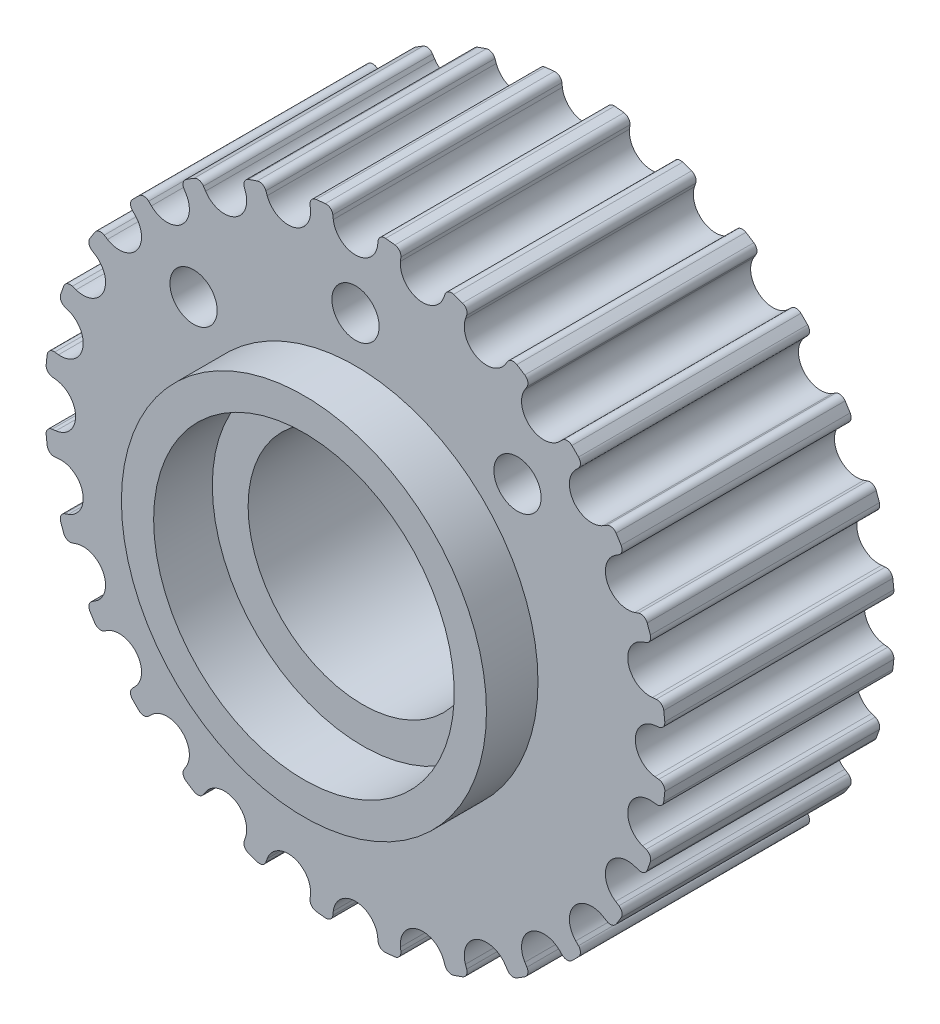
SolidWorks part; units mm, degrees
material "6061 合金"
ref_plane "前视基准面" through (0, 0, 0) normal (0, 0, 1) x (1, 0, 0)
ref_plane "上视基准面" through (0, 0, 0) normal (0, 1, 0) x (1, 0, 0)
ref_plane "右视基准面" through (0, 0, 0) normal (1, 0, 0) x (0, 0, -1)
sketch "草图2" plane through (0, 0, 0) normal (0, 0, 1) x (1, 0, 0)
  line L36 (1.3319, 20.7804) -> (1.2989, 20.5118)
  line L37 (-1.7978, 20.5118) -> (-1.8308, 20.7804)
  line L38 (-3.4222, 20.6011) -> (-3.3946, 20.3319)
  line L39 (-6.4137, 19.6428) -> (-6.5056, 19.8973)
  line L40 (-8.0172, 19.3684) -> (-7.9303, 19.1121)
  line L41 (-10.7204, 17.7684) -> (-10.8667, 17.9962)
  line L42 (-12.2227, 17.1441) -> (-12.081, 16.9135)
  line L43 (-14.5021, 14.9827) -> (-14.6954, 15.1722)
  line L44 (-15.8278, 14.0398) -> (-15.6383, 13.8465)
  line L45 (-17.5691, 11.4254) -> (-17.7997, 11.5671)
  line L46 (-18.6517, 10.2111) -> (-18.424, 10.0648)
  line L47 (-19.7676, 7.2748) -> (-20.024, 7.3616)
  line L48 (-20.5529, 5.85) -> (-20.2983, 5.7581)
  line L49 (-20.9874, 2.739) -> (-21.2567, 2.7666)
  line L50 (-21.436, 1.1752) -> (-21.1673, 1.1423)
  line L51 (-21.1673, -1.9545) -> (-21.436, -1.9875)
  line L52 (-21.2567, -3.5789) -> (-20.9874, -3.5512)
  line L53 (-20.2983, -6.5703) -> (-20.5529, -6.6623)
  line L54 (-20.024, -8.1739) -> (-19.7676, -8.087)
  line L55 (-18.424, -10.8771) -> (-18.6517, -11.0234)
  line L56 (-17.7997, -12.3793) -> (-17.5691, -12.2376)
  line L57 (-15.6383, -14.6588) -> (-15.8278, -14.8521)
  line L58 (-14.6954, -15.9845) -> (-14.5021, -15.795)
  line L59 (-12.081, -17.7258) -> (-12.2227, -17.9564)
  line L60 (-10.8667, -18.8084) -> (-10.7204, -18.5807)
  line L61 (-7.9303, -19.9243) -> (-8.0172, -20.1806)
  line L62 (-6.5056, -20.7096) -> (-6.4137, -20.455)
  line L63 (-3.3946, -21.1441) -> (-3.4222, -21.4133)
  line L64 (-1.8308, -21.5926) -> (-1.7978, -21.324)
  line L65 (1.2989, -21.324) -> (1.3319, -21.5926)
  line L66 (2.9233, -21.4133) -> (2.8957, -21.1441)
  line L67 (5.9148, -20.455) -> (6.0067, -20.7096)
  line L68 (7.5183, -20.1806) -> (7.4314, -19.9243)
  line L69 (10.2215, -18.5807) -> (10.3678, -18.8084)
  line L70 (11.7238, -17.9564) -> (11.5821, -17.7258)
  line L71 (14.0032, -15.795) -> (14.1965, -15.9845)
  line L72 (15.3289, -14.8521) -> (15.1394, -14.6588)
  line L73 (17.0702, -12.2376) -> (17.3008, -12.3793)
  line L74 (18.1528, -11.0234) -> (17.9251, -10.8771)
  line L75 (19.2687, -8.087) -> (19.5251, -8.1739)
  line L76 (20.054, -6.6623) -> (19.7994, -6.5703)
  line L77 (20.4885, -3.5512) -> (20.7578, -3.5789)
  line L78 (20.9371, -1.9875) -> (20.6684, -1.9545)
  line L79 (20.6684, 1.1423) -> (20.9371, 1.1752)
  line L80 (20.7578, 2.7666) -> (20.4885, 2.739)
  line L81 (19.7994, 5.7581) -> (20.054, 5.85)
  line L82 (19.5251, 7.3616) -> (19.2687, 7.2748)
  line L83 (17.9251, 10.0648) -> (18.1528, 10.2111)
  line L84 (17.3008, 11.5671) -> (17.0702, 11.4254)
  line L85 (15.1394, 13.8465) -> (15.3289, 14.0398)
  line L86 (14.1965, 15.1722) -> (14.0032, 14.9827)
  line L87 (11.5821, 16.9135) -> (11.7238, 17.1441)
  line L88 (10.3678, 17.9962) -> (10.2215, 17.7684)
  line L89 (7.4314, 19.1121) -> (7.5183, 19.3684)
  line L90 (6.0067, 19.8973) -> (5.9148, 19.6428)
  line L91 (2.8957, 20.3319) -> (2.9233, 20.6011)
  circle A72 centre (-0.2458, -0.3677) radius 12 construction
  circle A73 centre (-0.2458, -0.3677) radius 10.5
  arc A74 (2.9233, 20.6011) -> (2.5067, 21.1262) centre (2.4458, 20.6501) ccw
  arc A75 (2.5067, 21.1262) -> (1.8549, 21.1996) centre (-0.2495, -0.4061) ccw
  arc A76 (1.8549, 21.1996) -> (1.3319, 20.7804) centre (1.8083, 20.7219) ccw
  arc A77 (-1.7978, 20.5118) -> (1.2989, 20.5118) centre (-0.2495, 20.7019) ccw
  arc A78 (-1.8308, 20.7804) -> (-2.3538, 21.1996) centre (-2.3072, 20.7219) ccw
  arc A79 (-2.3538, 21.1996) -> (-3.0056, 21.1262) centre (-0.2495, -0.4061) ccw
  arc A80 (-3.0056, 21.1262) -> (-3.4222, 20.6011) centre (-2.9447, 20.6501) ccw
  arc A81 (-6.4137, 19.6428) -> (-3.3946, 20.3319) centre (-4.9464, 20.1727) ccw
  arc A82 (-6.5056, 19.8973) -> (-7.1087, 20.1897) centre (-6.9571, 19.7343) ccw
  arc A83 (-7.1087, 20.1897) -> (-7.7279, 19.973) centre (-0.2495, -0.4061) ccw
  arc A84 (-7.7279, 19.973) -> (-8.0172, 19.3684) centre (-7.5626, 19.5224) ccw
  arc A85 (-10.7204, 17.7684) -> (-7.9303, 19.1121) centre (-9.4079, 18.6115) ccw
  arc A86 (-10.8667, 17.9962) -> (-11.5198, 18.147) centre (-11.2706, 17.7367) ccw
  arc A87 (-11.5198, 18.147) -> (-12.0752, 17.798) centre (-0.2495, -0.4061) ccw
  arc A88 (-12.0752, 17.798) -> (-12.2227, 17.1441) centre (-11.8137, 17.3954) ccw
  arc A89 (-14.5021, 14.9827) -> (-12.081, 16.9135) centre (-13.4101, 16.0968) ccw
  arc A90 (-14.6954, 15.1722) -> (-15.3656, 15.1739) centre (-15.0314, 14.8294) ccw
  arc A91 (-15.3656, 15.1739) -> (-15.8295, 14.7101) centre (-0.2495, -0.4061) ccw
  arc A92 (-15.8295, 14.7101) -> (-15.8278, 14.0398) centre (-15.485, 14.3758) ccw
  arc A93 (-17.5691, 11.4254) -> (-15.6383, 13.8465) centre (-16.7524, 12.7545) ccw
  arc A94 (-17.7997, 11.5671) -> (-18.4535, 11.4196) centre (-18.051, 11.1582) ccw
  arc A95 (-18.4535, 11.4196) -> (-18.8026, 10.8642) centre (-0.2495, -0.4061) ccw
  arc A96 (-18.8026, 10.8642) -> (-18.6517, 10.2111) centre (-18.3923, 10.615) ccw
  arc A97 (-19.7676, 7.2748) -> (-18.424, 10.0648) centre (-19.2671, 8.7523) ccw
  arc A98 (-20.024, 7.3616) -> (-20.6286, 7.0724) centre (-20.178, 6.907) ccw
  arc A99 (-20.6286, 7.0724) -> (-20.8453, 6.4532) centre (-0.2495, -0.4061) ccw
  arc A100 (-20.8453, 6.4532) -> (-20.5529, 5.85) centre (-20.3899, 6.3015) ccw
  arc A101 (-20.9874, 2.739) -> (-20.2983, 5.7581) centre (-20.8282, 4.2909) ccw
  arc A102 (-21.2567, 2.7666) -> (-21.7818, 2.3501) centre (-21.3057, 2.2891) ccw
  arc A103 (-21.7818, 2.3501) -> (-21.8552, 1.6982) centre (-0.2495, -0.4061) ccw
  arc A104 (-21.8552, 1.6982) -> (-21.436, 1.1752) centre (-21.3775, 1.6517) ccw
  arc A105 (-21.1673, -1.9545) -> (-21.1673, 1.1423) centre (-21.3575, -0.4061) ccw
  arc A106 (-21.436, -1.9875) -> (-21.8552, -2.5104) centre (-21.3775, -2.4639) ccw
  arc A107 (-21.8552, -2.5104) -> (-21.7818, -3.1623) centre (-0.2495, -0.4061) ccw
  arc A108 (-21.7818, -3.1623) -> (-21.2567, -3.5789) centre (-21.3057, -3.1014) ccw
  arc A109 (-20.2983, -6.5703) -> (-20.9874, -3.5512) centre (-20.8282, -5.1031) ccw
  arc A110 (-20.5529, -6.6623) -> (-20.8453, -7.2654) centre (-20.3899, -7.1137) ccw
  arc A111 (-20.8453, -7.2654) -> (-20.6286, -7.8846) centre (-0.2495, -0.4061) ccw
  arc A112 (-20.6286, -7.8846) -> (-20.024, -8.1739) centre (-20.178, -7.7192) ccw
  arc A113 (-18.424, -10.8771) -> (-19.7676, -8.087) centre (-19.2671, -9.5645) ccw
  arc A114 (-18.6517, -11.0234) -> (-18.8026, -11.6764) centre (-18.3923, -11.4272) ccw
  arc A115 (-18.8026, -11.6764) -> (-18.4535, -12.2319) centre (-0.2495, -0.4061) ccw
  arc A116 (-18.4535, -12.2319) -> (-17.7997, -12.3793) centre (-18.051, -11.9704) ccw
  arc A117 (-15.6383, -14.6588) -> (-17.5691, -12.2376) centre (-16.7524, -13.5667) ccw
  arc A118 (-15.8278, -14.8521) -> (-15.8295, -15.5223) centre (-15.485, -15.1881) ccw
  arc A119 (-15.8295, -15.5223) -> (-15.3656, -15.9862) centre (-0.2495, -0.4061) ccw
  arc A120 (-15.3656, -15.9862) -> (-14.6954, -15.9845) centre (-15.0314, -15.6417) ccw
  arc A121 (-12.081, -17.7258) -> (-14.5021, -15.795) centre (-13.4101, -16.909) ccw
  arc A122 (-12.2227, -17.9564) -> (-12.0752, -18.6102) centre (-11.8137, -18.2077) ccw
  arc A123 (-12.0752, -18.6102) -> (-11.5198, -18.9592) centre (-0.2495, -0.4061) ccw
  arc A124 (-11.5198, -18.9592) -> (-10.8667, -18.8084) centre (-11.2706, -18.549) ccw
  arc A125 (-7.9303, -19.9243) -> (-10.7204, -18.5807) centre (-9.4079, -19.4238) ccw
  arc A126 (-8.0172, -20.1806) -> (-7.7279, -20.7853) centre (-7.5626, -20.3347) ccw
  arc A127 (-7.7279, -20.7853) -> (-7.1087, -21.0019) centre (-0.2495, -0.4061) ccw
  arc A128 (-7.1087, -21.0019) -> (-6.5056, -20.7096) centre (-6.9571, -20.5465) ccw
  arc A129 (-3.3946, -21.1441) -> (-6.4137, -20.455) centre (-4.9464, -20.9849) ccw
  arc A130 (-3.4222, -21.4133) -> (-3.0056, -21.9384) centre (-2.9447, -21.4623) ccw
  arc A131 (-3.0056, -21.9384) -> (-2.3538, -22.0119) centre (-0.2495, -0.4061) ccw
  arc A132 (-2.3538, -22.0119) -> (-1.8308, -21.5926) centre (-2.3072, -21.5341) ccw
  arc A133 (1.2989, -21.324) -> (-1.7978, -21.324) centre (-0.2495, -21.5141) ccw
  arc A134 (1.3319, -21.5926) -> (1.8549, -22.0119) centre (1.8083, -21.5341) ccw
  arc A135 (1.8549, -22.0119) -> (2.5067, -21.9384) centre (-0.2495, -0.4061) ccw
  arc A136 (2.5067, -21.9384) -> (2.9233, -21.4133) centre (2.4458, -21.4623) ccw
  arc A137 (5.9148, -20.455) -> (2.8957, -21.1441) centre (4.4475, -20.9849) ccw
  arc A138 (6.0067, -20.7096) -> (6.6098, -21.0019) centre (6.4582, -20.5465) ccw
  arc A139 (6.6098, -21.0019) -> (7.229, -20.7853) centre (-0.2495, -0.4061) ccw
  arc A140 (7.229, -20.7853) -> (7.5183, -20.1806) centre (7.0637, -20.3347) ccw
  arc A141 (10.2215, -18.5807) -> (7.4314, -19.9243) centre (8.909, -19.4238) ccw
  arc A142 (10.3678, -18.8084) -> (11.0209, -18.9592) centre (10.7716, -18.549) ccw
  arc A143 (11.0209, -18.9592) -> (11.5763, -18.6102) centre (-0.2495, -0.4061) ccw
  arc A144 (11.5763, -18.6102) -> (11.7238, -17.9564) centre (11.3148, -18.2077) ccw
  arc A145 (14.0032, -15.795) -> (11.5821, -17.7258) centre (12.9112, -16.909) ccw
  arc A146 (14.1965, -15.9845) -> (14.8667, -15.9862) centre (14.5325, -15.6417) ccw
  arc A147 (14.8667, -15.9862) -> (15.3306, -15.5223) centre (-0.2495, -0.4061) ccw
  arc A148 (15.3306, -15.5223) -> (15.3289, -14.8521) centre (14.9861, -15.1881) ccw
  arc A149 (17.0702, -12.2376) -> (15.1394, -14.6588) centre (16.2534, -13.5667) ccw
  arc A150 (17.3008, -12.3793) -> (17.9546, -12.2319) centre (17.5521, -11.9704) ccw
  arc A151 (17.9546, -12.2319) -> (18.3036, -11.6764) centre (-0.2495, -0.4061) ccw
  arc A152 (18.3036, -11.6764) -> (18.1528, -11.0234) centre (17.8934, -11.4272) ccw
  arc A153 (19.2687, -8.087) -> (17.9251, -10.8771) centre (18.7682, -9.5645) ccw
  arc A154 (19.5251, -8.1739) -> (20.1297, -7.8846) centre (19.6791, -7.7192) ccw
  arc A155 (20.1297, -7.8846) -> (20.3464, -7.2654) centre (-0.2495, -0.4061) ccw
  arc A156 (20.3464, -7.2654) -> (20.054, -6.6623) centre (19.891, -7.1137) ccw
  arc A157 (20.4885, -3.5512) -> (19.7994, -6.5703) centre (20.3293, -5.1031) ccw
  arc A158 (20.7578, -3.5789) -> (21.2829, -3.1623) centre (20.8067, -3.1014) ccw
  arc A159 (21.2829, -3.1623) -> (21.3563, -2.5104) centre (-0.2495, -0.4061) ccw
  arc A160 (21.3563, -2.5104) -> (20.9371, -1.9875) centre (20.8786, -2.4639) ccw
  arc A161 (20.6684, 1.1423) -> (20.6684, -1.9545) centre (20.8585, -0.4061) ccw
  arc A162 (20.9371, 1.1752) -> (21.3563, 1.6982) centre (20.8786, 1.6517) ccw
  arc A163 (21.3563, 1.6982) -> (21.2829, 2.3501) centre (-0.2495, -0.4061) ccw
  arc A164 (21.2829, 2.3501) -> (20.7578, 2.7666) centre (20.8067, 2.2891) ccw
  arc A165 (19.7994, 5.7581) -> (20.4885, 2.739) centre (20.3293, 4.2909) ccw
  arc A166 (20.054, 5.85) -> (20.3464, 6.4532) centre (19.891, 6.3015) ccw
  arc A167 (20.3464, 6.4532) -> (20.1297, 7.0724) centre (-0.2495, -0.4061) ccw
  arc A168 (20.1297, 7.0724) -> (19.5251, 7.3616) centre (19.6791, 6.907) ccw
  arc A169 (17.9251, 10.0648) -> (19.2687, 7.2748) centre (18.7682, 8.7523) ccw
  arc A170 (18.1528, 10.2111) -> (18.3036, 10.8642) centre (17.8934, 10.615) ccw
  arc A171 (18.3036, 10.8642) -> (17.9546, 11.4196) centre (-0.2495, -0.4061) ccw
  arc A172 (17.9546, 11.4196) -> (17.3008, 11.5671) centre (17.5521, 11.1582) ccw
  arc A173 (15.1394, 13.8465) -> (17.0702, 11.4254) centre (16.2534, 12.7545) ccw
  arc A174 (15.3289, 14.0398) -> (15.3306, 14.7101) centre (14.9861, 14.3758) ccw
  arc A175 (15.3306, 14.7101) -> (14.8667, 15.1739) centre (-0.2495, -0.4061) ccw
  arc A176 (14.8667, 15.1739) -> (14.1965, 15.1722) centre (14.5325, 14.8294) ccw
  arc A177 (11.5821, 16.9135) -> (14.0032, 14.9827) centre (12.9112, 16.0968) ccw
  arc A178 (11.7238, 17.1441) -> (11.5763, 17.798) centre (11.3148, 17.3954) ccw
  arc A179 (11.5763, 17.798) -> (11.0209, 18.147) centre (-0.2495, -0.4061) ccw
  arc A180 (11.0209, 18.147) -> (10.3678, 17.9962) centre (10.7716, 17.7367) ccw
  arc A181 (7.4314, 19.1121) -> (10.2215, 17.7684) centre (8.909, 18.6115) ccw
  arc A182 (7.5183, 19.3684) -> (7.229, 19.973) centre (7.0637, 19.5224) ccw
  arc A183 (7.229, 19.973) -> (6.6098, 20.1897) centre (-0.2495, -0.4061) ccw
  arc A184 (6.6098, 20.1897) -> (6.0067, 19.8973) centre (6.4582, 19.7343) ccw
  arc A185 (2.8957, 20.3319) -> (5.9148, 19.6428) centre (4.4475, 20.1727) ccw
  dimension "D1" = 21
extrude "凸台-拉伸1" add sketch "草图2" along normal blind 16
move or copy body "实体-移动/复制1" bodies to move or copy 106 copy no translate (-21.7751, 0, 0) parameters "D1"=21.7751, "D2"=0, "D3"=0
sketch "草图12" plane through (0, 0, 16) normal (0, 0, 1) x (1, 0, 0)
  circle A0 centre (-22.0209, -0.3677) radius 10.5 construction
  circle A1 centre (-22.0209, -0.3677) radius 10.5
  circle A2 centre (-22.0246, -0.3096) radius 11.5
  circle A3 centre (-22.0246, -0.3096) radius 13
  circle A4 centre (-22.0209, -0.3677) radius 16
  point P7 (-6.0209, -0.3677)
  point P10 (-10.7072, -11.6815)
  point P11 (-22.0209, -16.3677)
  point P12 (-33.3346, -11.6815)
  point P13 (-38.0209, -0.3677)
  point P14 (-33.3346, 10.946)
  point P15 (-22.0209, 15.6323)
  point P16 (-10.7072, 10.946)
  point P17 (-22.0209, -0.3677)
  dimension "D1" = 23
  dimension "D2" = 26
  dimension "D3" = 32
  dimension "D4" = 8
extrude "凸台-拉伸2" add sketch "草图12" along normal blind 4 and the other way blind 18 contours A3 A2
sketch "草图14" plane through (0, 0, 16) normal (0, 0, 1) x (1, 0, 0)
  circle A0 centre (-22.0209, -0.3677) radius 10.5 construction
  circle A1 centre (-22.0246, -0.3096) radius 11.5
  circle A2 centre (-22.0246, -0.3096) radius 11.5
  circle A3 centre (-22.0209, -0.3677) radius 10.5
  dimension "D1" = 0
extrude "切除-拉伸1" cut sketch "草图14" against normal blind 1.1
sketch "草图15" plane through (0, 0, 16) normal (0, 0, 1) x (1, 0, 0)
  circle A0 centre (-22.0209, -0.3677) radius 16 construction
  circle A1 centre (-22.0209, -0.3677) radius 16 construction
  circle A2 centre (-22.0209, 15.6323) radius 4.05
  circle A3 centre (-10.7072, 10.946) radius 4.05
  circle A4 centre (-6.0209, -0.3677) radius 4.05 [skipped]
  circle A8 centre (-38.0209, -0.3677) radius 4.05 [skipped]
  circle A9 centre (-33.3346, 10.946) radius 4.05
  circle A10 centre (-10.7072, -11.6815) radius 4.05 [skipped]
  circle A11 centre (-33.3346, -11.6815) radius 4.05 [skipped]
  circle A12 centre (-22.0209, -16.3677) radius 4.05 [skipped]
  point P0 (-33.3346, -11.6815)
  point P2 (-22.0209, -16.3677)
  point P4 (-10.7072, -11.6815)
  point P6 (-10.7072, 10.946)
  point P8 (-22.0209, 15.6323)
  point P10 (-33.3346, 10.946)
  point P34 (-22.0209, -0.3677)
  dimension "D1" = 8.1
  dimension "D2" = 8
sketch "草图16" plane through (0, 0, 0) normal (0, 0, -1) x (-1, 0, 0)
  circle A0 centre (22.0209, -0.3677) radius 10.5 construction
  circle A1 centre (22.0246, -0.3096) radius 11.5
  circle A2 centre (22.0246, -0.3096) radius 11.5
  circle A3 centre (22.0209, -0.3677) radius 10.5
  dimension "D1" = 0
sketch "草图18" plane through (0, 0, 0) normal (0, 0, -1) x (-1, 0, 0)
  line L0 (22.0209, -0.3677) -> (22.0209, 21.2599) construction
  line L1 (22.0209, -0.3677) -> (3.1451, 18.5081) construction
  line L2 (22.0209, -0.3677) -> (38.7709, 16.3822) construction
  circle A0 centre (22.0209, -0.3677) radius 16 construction
  circle A1 centre (10.7072, 10.946) radius 1.65
  circle A3 centre (22.0209, 15.6323) radius 1.65
  circle A4 centre (33.3346, 10.946) radius 1.65
  circle A5 centre (22.0209, -0.3677) radius 12.9417 construction
  point P14 (33.3346, 10.946)
  dimension "D1" = 32
  dimension "D3" = 3.3
  dimension "D4" = 3.3
  dimension "D6" = 3.3
  dimension "D2" = 45
  dimension "D5" = 45
extrude "切除-拉伸5" cut sketch "草图16" against normal blind 1.1
sketch "草图20" plane through (0, 0, 20) normal (0, 0, 1) x (1, 0, 0)
  circle A0 centre (-22.0246, -0.3096) radius 11.9673
extrude "凸台-拉伸3" add sketch "草图20" against normal up to surface (22 mm away) up to face at (-10.5246, -0.3096, -2)
sketch "草图21" plane through (0, 0, -2) normal (0, 0, -1) x (-1, 0, 0)
  circle A0 centre (22.0246, -0.3096) radius 13
extrude "凸台-拉伸4" add sketch "草图21" along normal blind 1
sketch "草图22" plane through (0, 0, -3) normal (0, 0, -1) x (-1, 0, 0)
  circle A0 centre (22.0246, -0.3096) radius 11.5
  circle A1 centre (22.0246, -0.3096) radius 8.5
  dimension "D1" = 23
  dimension "D2" = 17
extrude "切除-拉伸6" cut sketch "草图22" against normal blind 4.1
sketch "草图23" plane through (0, 0, -3) normal (0, 0, -1) x (-1, 0, 0)
  circle A0 centre (22.0246, -0.3096) radius 8.5
extrude "切除-拉伸7" cut sketch "草图23" against normal blind 33.1
sketch "草图24" plane through (0, 0, 20) normal (0, 0, 1) x (1, 0, 0)
  circle A0 centre (-22.0246, -0.3096) radius 11.5
  dimension "D1" = 23
extrude "切除-拉伸8" cut sketch "草图24" against normal blind 4.1
sketch "草图25" plane through (0, 0, -3) normal (0, 0, -1) x (-1, 0, 0)
  circle A0 centre (22.0246, -0.3096) radius 14.3512
extrude "切除-拉伸9" cut sketch "草图25" against normal blind 35
sketch "草图26" plane through (0, 0, 0) normal (0, 0, -1) x (-1, 0, 0)
  circle A0 centre (22.0246, -0.3096) radius 14.8679
extrude "凸台-拉伸5" add sketch "草图26" against normal up to surface (16 mm away) up to face at (-7.6733, -0.3096, 16)
sketch "草图27" plane through (0, 0, 0) normal (0, 0, -1) x (-1, 0, 0)
  circle A0 centre (22.0246, -0.3096) radius 8
  dimension "D1" = 16
extrude "切除-拉伸10" cut sketch "草图27" against normal blind 27
sketch "草图30" plane through (0, 0, 0) normal (0, 0, -1) x (-1, 0, 0)
  circle A0 centre (22.0246, -0.3096) radius 10.5
  circle A1 centre (22.0246, -0.3096) radius 12.75
  dimension "D1" = 21
  dimension "D2" = 25.5
extrude "凸台-拉伸6" add sketch "草图30" along normal blind 3.6 contours A1 | A0
sketch "草图31" plane through (0, 0, 0) normal (0, 0, -1) x (-1, 0, 0)
  circle A1 centre (22.0246, -0.3096) radius 10.5
extrude "切除-拉伸13" cut sketch "草图31" against normal blind 0.5
ref_plane "基准面2" through (0, 0, 8) normal (0, 0, -1) x (-1, 0, 0)
mirror "镜向2" about plane through (0, 0, 8) normal (0, 0, -1) of "切除-拉伸13", "凸台-拉伸6"
extrude "切除-拉伸15" cut sketch "草图18" against normal blind 25
